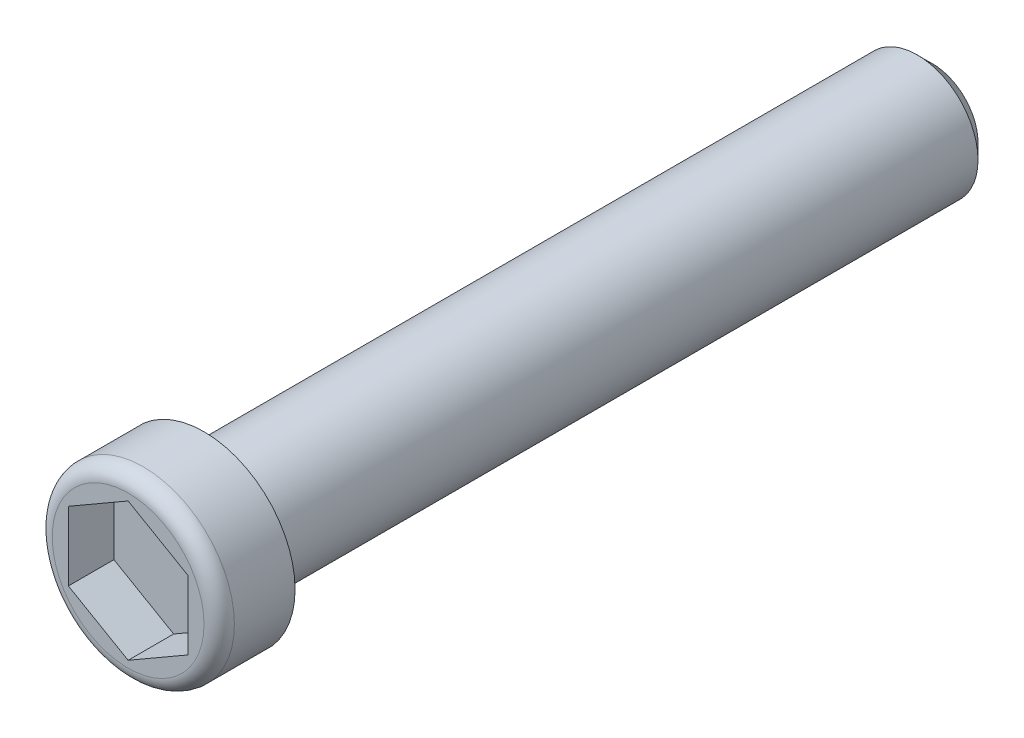
SolidWorks part; units mm, degrees
ref_plane "前视基准面" through (0, 0, 0) normal (0, 0, 1) x (1, 0, 0)
ref_plane "上视基准面" through (0, 0, 0) normal (0, 1, 0) x (1, 0, 0)
ref_plane "右视基准面" through (0, 0, 0) normal (1, 0, 0) x (0, 0, -1)
sketch "草图1" plane through (0, 0, 0) normal (0, 0, 1) x (1, 0, 0)
  circle A0 centre (0, 0) radius 2
extrude "凸台-拉伸1" add sketch "草图1" along normal blind 24
sketch "草图2" plane through (0, 0, 24) normal (0, 0, 1) x (1, 0, 0)
  circle A0 centre (0, 0) radius 3
extrude "凸台-拉伸2" add sketch "草图2" along normal blind 2.5
sketch "草图3" plane through (0, 0, 26.5) normal (0, 0, 1) x (1, 0, 0)
  line L1 (0, 2.2728) -> (-1.9683, 1.1364)
  line L2 (-1.9683, 1.1364) -> (-1.9683, -1.1364)
  line L3 (-1.9683, -1.1364) -> (0, -2.2728)
  line L4 (0, -2.2728) -> (1.9683, -1.1364)
  line L5 (1.9683, -1.1364) -> (1.9683, 1.1364)
  line L6 (1.9683, 1.1364) -> (0, 2.2728)
  circle A0 centre (0, 0) radius 1.9683 construction
extrude "切除-拉伸1" cut sketch "草图3" against normal blind 1.5
fillet "圆角1" radius 0.5 1 edges at (3, 0, 26.5)
chamfer "倒角1" distance 0.5 angle 45 1 edges at (2, 0, 0)
